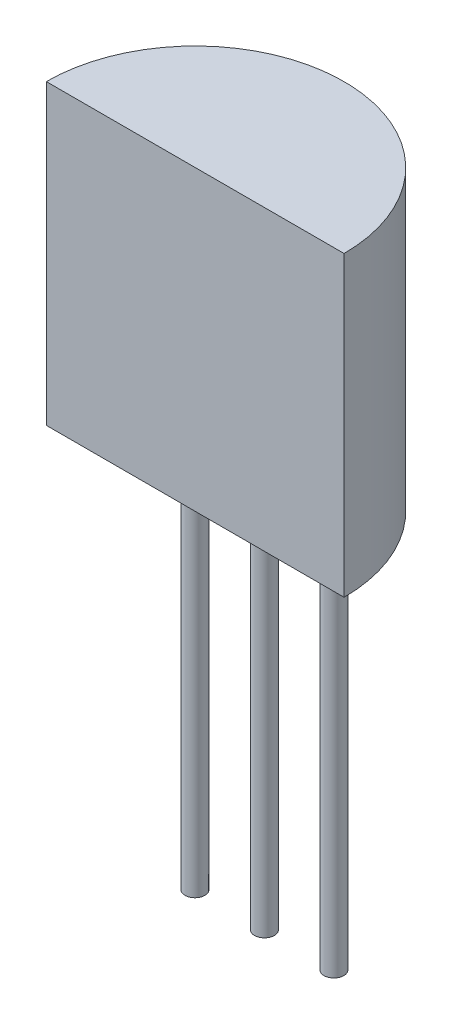
SolidWorks part; units mm, degrees
ref_plane "Ön Düzlem" through (0, 0, 0) normal (0, 0, 1) x (1, 0, 0)
ref_plane "Üst Düzlem" through (0, 0, 0) normal (0, 1, 0) x (1, 0, 0)
ref_plane "Sağ Düzlem" through (0, 0, 0) normal (1, 0, 0) x (0, 0, -1)
sketch "Çizim1" plane through (0, 0, 0) normal (0, 1, 0) x (1, 0, 0)
  line L0 (0, 0) -> (15, 0)
  arc A2 (15, 0) -> (0, 0) centre (7.5, 0) ccw
  dimension "D1" = 7.5
extrude "Yükseklik-Ekstrüzyon1" add sketch "Çizim1" along normal blind 15
sketch "Çizim3" plane through (0, 15, 0) normal (0, 1, 0) x (1, 0, 0)
  line L0 (7.5, 0) -> (7.5, 7.5)
  line L1 (0, 0) -> (15, 0) construction
  arc A0 (15, 0) -> (0, 0) centre (7.5, 0) ccw construction
ref_plane "Düzlem1" through (7.5, 15, -7.5) normal (0, 0, -1) x (-1, 0, 0)
sketch "Çizim4" plane through (7.5, 15, -7.5) normal (0, 0, -1) x (-1, 0, 0)
  line L0 (-7.5, -15) -> (7.5, -15) construction
  circle A0 centre (0, -7.5) radius 3
  dimension "D1" = 6
  dimension "D2" = 7.5
extrude "Kes-Ekstrüzyon1" cut sketch "Çizim4" against normal blind 2
sketch "Çizim6" plane through (0, 0, 0) normal (0, -1, 0) x (1, 0, 0)
  line L0 (7.5, -3.75) -> (1.0048, -3.75)
  line L1 (7.5, 0) -> (7.5, -7.5) construction
  line L2 (7.5, -3.75) -> (13.9952, -3.75)
  line L3 (7.5, -3.4886) -> (11, -3.4886)
  line L4 (7, -3.4886) -> (4, -3.4886)
  arc A0 (0, 0) -> (15, 0) centre (7.5, 0) ccw construction
  circle A1 centre (11, -3.4886) radius 0.5
  circle A2 centre (7.5, -3.4886) radius 0.5
  circle A3 centre (4, -3.4886) radius 0.5
  dimension "D2" = 1
  dimension "D3" = 1
  dimension "D5" = 1
  dimension "D1" = 3.5
  dimension "D4" = 3
sketch3d "3B Çizim2"
  line L0 (4, 0, -3.4886) -> (4, -20, -3.4886)
  line L1 (7.5, 0, -3.4886) -> (7.5, -20, -3.4886)
  line L2 (11, 0, -3.4886) -> (11, -20, -3.4886)
  dimension "D1" = 20
  dimension "D2" = 20
  dimension "D3" = 20
ref_plane "Düzlem2" through (4, -20, -3.4886) normal (0, -1, 0) x (-1, 0, 0)
sketch "Çizim8" plane through (4, -20, -3.4886) normal (0, -1, 0) x (-1, 0, 0)
  circle A0 centre (-7, 0) radius 0.5
sweep "Süpür1" add profiles "Çizim8" path "3B Çizim2"
sketch3d "3B Çizim3"
  line L0 (7.5, 0, -3.4886) -> (7.5, -20, -3.4886)
  dimension "D1" = 20
sketch "Çizim10" plane through (4, -20, -3.4886) normal (0, -1, 0) x (-1, 0, 0)
  circle A0 centre (-3.5, 0) radius 0.5
  dimension "D1" = 1
sweep "Süpür2" add profiles "Çizim10" path "3B Çizim3"
sketch3d "3B Çizim4"
  line L0 (4, 0, -3.4886) -> (4, -20, -3.4886)
  dimension "D1" = 20
sketch "Çizim11" plane through (4, -20, -3.4886) normal (0, -1, 0) x (-1, 0, 0)
  circle A0 centre (0, 0) radius 0.5
sweep "Süpür3" add profiles "Çizim11" path "3B Çizim4"
